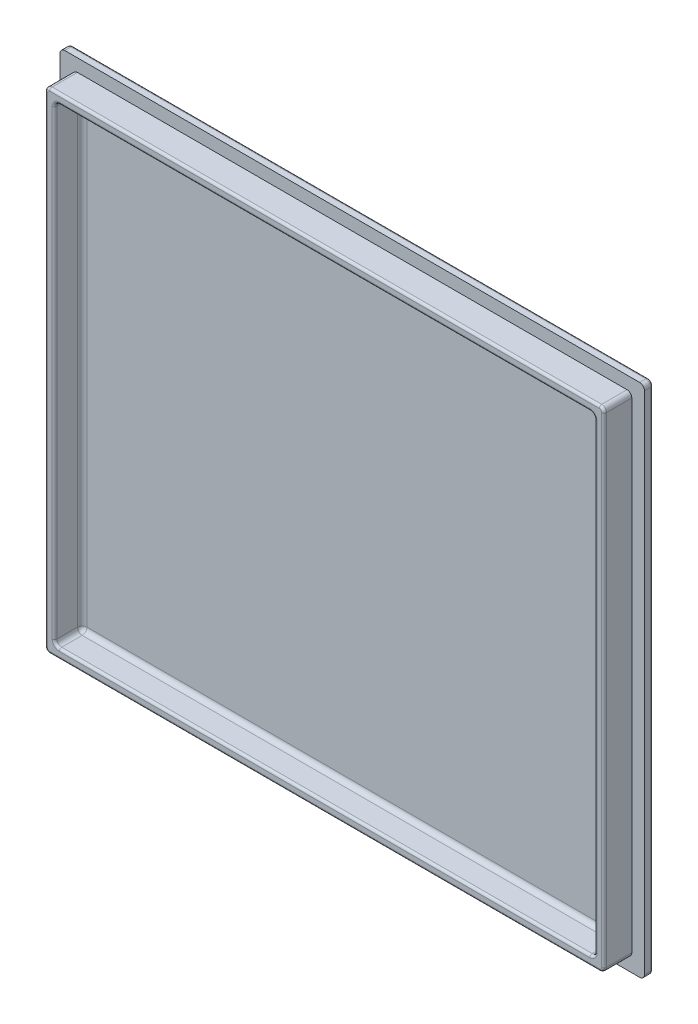
SolidWorks part; units mm, degrees
ref_plane "Front Plane" through (0, 0, 0) normal (0, 0, 1) x (1, 0, 0)
ref_plane "Top Plane" through (0, 0, 0) normal (0, 1, 0) x (1, 0, 0)
ref_plane "Right Plane" through (0, 0, 0) normal (1, 0, 0) x (0, 0, -1)
sketch "Sketch1" plane through (0, 0, 0) normal (0, 0, 1) x (1, 0, 0)
  line L1 (-61.25, 54) -> (61.25, 54)
  line L2 (-61.25, 54) -> (-61.25, -54)
  line L3 (-61.25, -54) -> (61.25, -54)
  line L4 (61.25, 54) -> (61.25, -54)
  line L5 (-61.25, 54) -> (61.25, -54) construction
  line L6 (-61.25, -54) -> (61.25, 54) construction
  point P0 (0, 0)
  dimension "D1" = 108
  dimension "D2" = 122.5
extrude "Boss-Extrude1" add sketch "Sketch1" along normal blind 1.8
sketch "Sketch2" plane through (0, 0, 1.8) normal (0, 0, 1) x (1, 0, 0)
  line L0 (61.25, 54) -> (-61.25, 54) construction
  line L1 (58.6, -51.35) -> (-58.6, -51.35)
  line L2 (58.6, -51.35) -> (58.6, 51.35)
  line L3 (58.6, 51.35) -> (-58.6, 51.35)
  line L4 (-58.6, -51.35) -> (-58.6, 51.35)
  line L5 (58.6, -51.35) -> (-58.6, 51.35) construction
  line L6 (58.6, 51.35) -> (-58.6, -51.35) construction
  line L7 (61.25, -54) -> (61.25, 54) construction
  line L9 (56.6, -49.35) -> (-56.6, -49.35)
  line L10 (56.6, -49.35) -> (56.6, 49.35)
  line L11 (56.6, 49.35) -> (-56.6, 49.35)
  line L12 (-56.6, -49.35) -> (-56.6, 49.35)
  line L13 (56.6, -49.35) -> (-56.6, 49.35) construction
  line L14 (56.6, 49.35) -> (-56.6, -49.35) construction
  point P0 (0, 0)
  point P10 (0, 0)
  dimension "D1" = 2.65
  dimension "D2" = 2.65
  dimension "D3" = 2
  dimension "D4" = 2
extrude "Boss-Extrude2" add sketch "Sketch2" along normal blind 5.8
fillet "Fillet1" radius 1 16 edges at (-61.25, -54, 0.9) (-61.25, 54, 0.9) (61.25, -54, 0.9) (56.6, -49.35, 4.7) (56.6, 49.35, 4.7) (-56.6, 49.35, 4.7) (-56.6, -49.35, 4.7) (-58.6, 51.35, 4.7) (58.6, -51.35, 4.7) (-58.6, -51.35, 4.7) (58.6, 51.35, 4.7) (61.25, 54, 0.9) (0, 49.35, 1.8) (56.6, 0, 1.8) (0, -49.35, 1.8) (-56.6, 0, 1.8)
fillet "Fillet2" radius 0.5 24 edges at (60.9571, -53.7071, 0) (61.25, 0, 0) (60.9571, 53.7071, 0) (0, 54, 0) (-60.9571, 53.7071, 0) (-61.25, 0, 0) (-60.9571, -53.7071, 0) (0, -54, 0) (56.3071, -49.0571, 7.6) (56.6, 0, 7.6) (56.3071, 49.0571, 7.6) (0, 49.35, 7.6) (-56.3071, 49.0571, 7.6) (-56.6, 0, 7.6) (-56.3071, -49.0571, 7.6) (0, -49.35, 7.6) (58.3071, 51.0571, 7.6) (58.6, 0, 7.6) (58.3071, -51.0571, 7.6) (0, -51.35, 7.6) (-58.3071, -51.0571, 7.6) (-58.6, 0, 7.6) (-58.3071, 51.0571, 7.6) (0, 51.35, 7.6)
sketch "Sketch3" plane through (0, 0, 0) normal (0, 0, -1) x (-1, 0, 0)
  line L0 (-61.25, 0) -> (61.25, 0) construction
  line L1 (-61.25, -53) -> (-61.25, 53) construction
  line L2 (61.25, 53) -> (61.25, -53) construction
  line L3 (-60.75, 9) -> (60.75, 9) construction
  line L4 (-60.75, 53) -> (-60.75, -53) construction
  line L5 (60.75, -53) -> (60.75, 53) construction
  text T0 "JOULEMETER\r\n100V DC\r\n20A DC" font "Arial Rounded MT Bold" height 7.5
  dimension "D1" = 9
extrude "Cut-Extrude1" cut sketch "Sketch3" against normal blind 0.4
